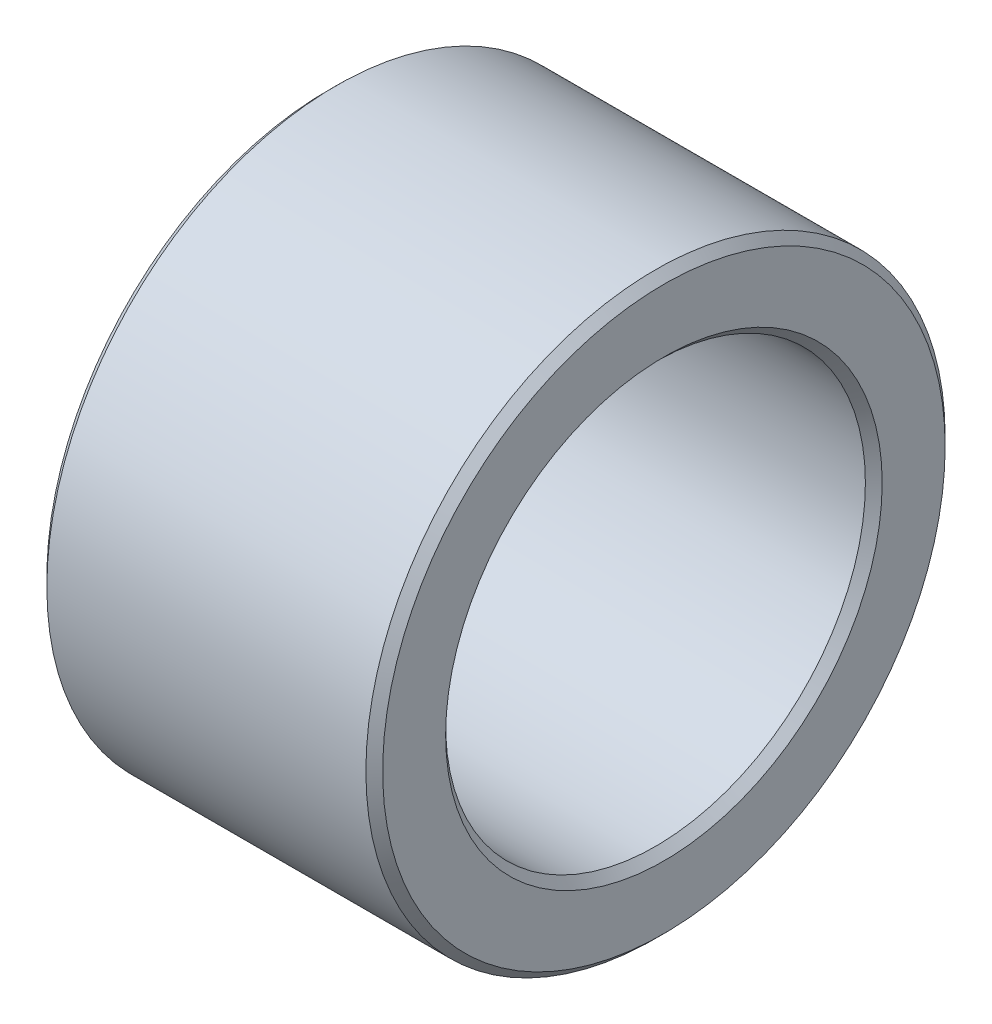
SolidWorks part; units mm, degrees
other "标注1"
sketch "草图2" plane through (0, 3.5, -3.5) normal (-0.2968, 0.4965, -0.8157) x (0.5922, -0.5744, -0.5651)
other "标注2"
sketch "草图3" plane through (0, 3.5, -3.5) normal (-0.2968, 0.4965, -0.8157) x (0.5922, -0.5744, -0.5651)
material "AISI 304"
ref_plane "前视基准面" through (0, 0, 0) normal (1, 0, 0) x (0, 1, 0)
ref_plane "上视基准面" through (0, 0, 0) normal (0, 0, 1) x (0, 1, 0)
ref_plane "右视基准面" through (0, 0, 0) normal (0, 1, 0) x (-1, 0, 0)
other "Configuration Table"
sketch "草图1" plane through (0, 0, 0) normal (1, 0, 0) x (0, 1, 0)
  circle A0 centre (0, 0) radius 3.45
  circle A1 centre (0, 0) radius 2.5
  dimension "D1" = 6.9
  dimension "D2" = 5
extrude "凸台-拉伸1" add sketch "草图1" along normal blind 4
chamfer "倒角1" distance 0.1 angle 45 4 edges at (4, 0, -2.5) (0, 0, -2.5) (0, 0, -3.45) (4, 0, -3.45)
